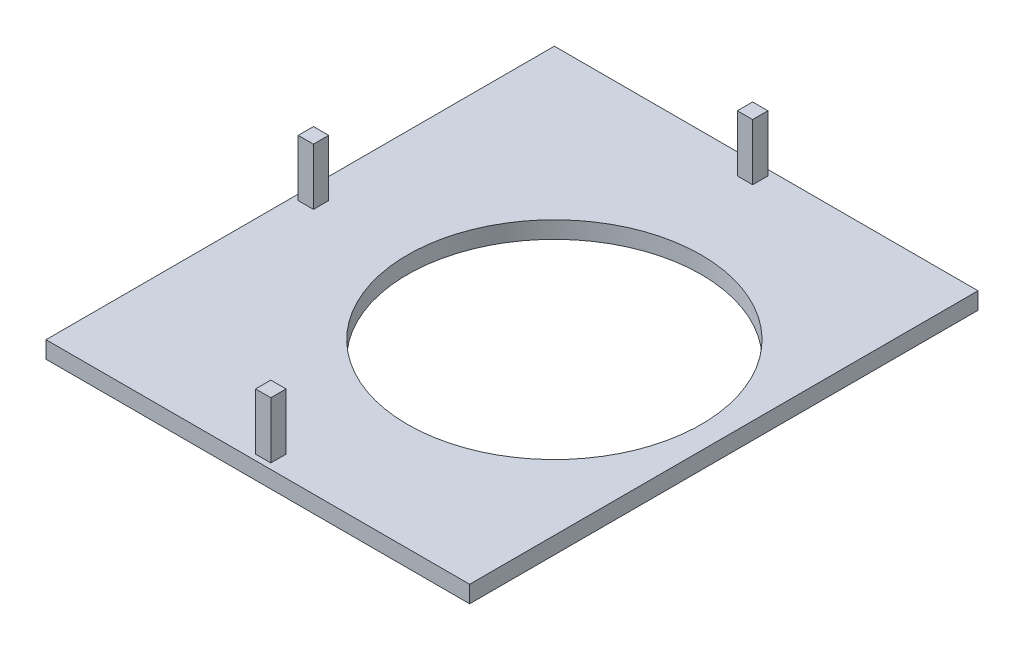
SolidWorks part; units mm, degrees
ref_plane "Front Plane" through (0, 0, 0) normal (0, 0, 1) x (1, 0, 0)
ref_plane "Top Plane" through (0, 0, 0) normal (0, 1, 0) x (1, 0, 0)
ref_plane "Right Plane" through (0, 0, 0) normal (1, 0, 0) x (0, 0, -1)
sketch "Sketch1" plane through (0, 0, 0) normal (0, 1, 0) x (1, 0, 0)
  line L1 (0, 0) -> (75, 0)
  line L2 (0, 0) -> (0, -90)
  line L3 (0, -90) -> (75, -90)
  line L4 (75, 0) -> (75, -90)
  dimension "D1" = 75
  dimension "D2" = 90
extrude "Boss-Extrude1" add sketch "Sketch1" along normal blind 3
sketch "Sketch2" plane through (0, 3, 0) normal (0, 1, 0) x (1, 0, 0)
  line L0 (75, 0) -> (0, 0) construction
  line L1 (36.1, -1) -> (38.8, -1)
  line L2 (36.1, -1) -> (36.1, -3.7)
  line L3 (36.1, -3.7) -> (38.8, -3.7)
  line L4 (38.8, -1) -> (38.8, -3.7)
  line L5 (1, -43.65) -> (3.7, -43.65)
  line L6 (1, -43.65) -> (1, -46.35)
  line L7 (1, -46.35) -> (3.7, -46.35)
  line L8 (3.7, -43.65) -> (3.7, -46.35)
  line L9 (36.1, -86.3) -> (38.8, -86.3)
  line L10 (36.1, -86.3) -> (36.1, -89)
  line L11 (36.1, -89) -> (38.8, -89)
  line L12 (38.8, -86.3) -> (38.8, -89)
  line L13 (0, -90) -> (75, -90) construction
  line L14 (0, 0) -> (0, -90) construction
  line L15 (2.35, -43.65) -> (2.35, 0) construction
  line L16 (2.35, -46.35) -> (2.35, -90) construction
  dimension "D1" = 2.7
  dimension "D2" = 1
  dimension "D3" = 1
  dimension "D4" = 36.1
  dimension "D5" = 1
extrude "Boss-Extrude2" add sketch "Sketch2" along normal blind 10
sketch "Sketch3" plane through (0, 3, 0) normal (0, 1, 0) x (1, 0, 0)
  line L0 (0, 0) -> (0, -90) construction
  circle A0 centre (45, -45) radius 26
  dimension "D1" = 52
  dimension "D2" = 45
extrude "Cut-Extrude1" cut sketch "Sketch3" against normal up to surface (3 mm away) up to face at (37.5, 0, 45)
